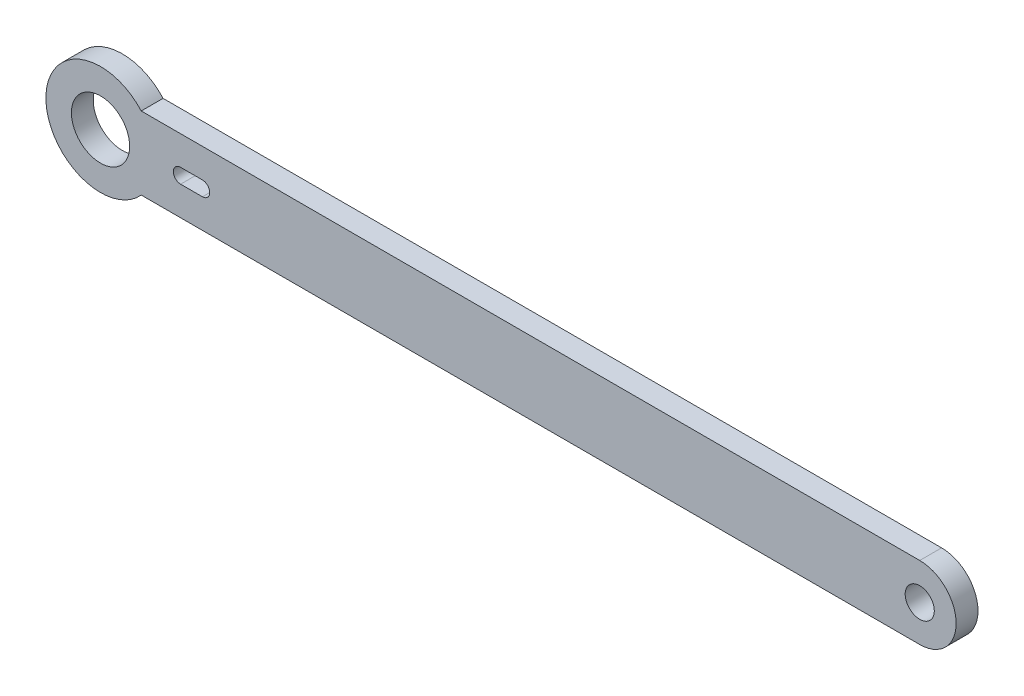
SolidWorks part; units mm, degrees
ref_plane "前视基准面" through (0, 0, 0) normal (0, 0, 1) x (1, 0, 0)
ref_plane "上视基准面" through (0, 0, 0) normal (0, 1, 0) x (1, 0, 0)
ref_plane "右视基准面" through (0, 0, 0) normal (1, 0, 0) x (0, 0, -1)
sketch "草图1" plane through (0, 0, 0) normal (0, 0, 1) x (1, 0, 0)
  line L0 (0, 0) -> (112.5, 0) construction
  line L1 (1.65, 0) -> (-1.65, 0) construction
  line L2 (5.5902, 5) -> (112.5, 5)
  line L3 (5.5902, -5) -> (112.5, -5)
  line L4 (11, 0) -> (14, 0) construction
  line L5 (11, 1) -> (14, 1)
  line L6 (11, -1) -> (14, -1)
  arc A1 (112.5, -5) -> (112.5, 5) centre (112.5, 0) ccw
  circle A2 centre (112.5, 0) radius 2
  circle A3 centre (0, 0) radius 4
  arc A4 (5.5902, 5) -> (5.5902, -5) centre (0, 0) ccw
  arc A5 (11, 1) -> (11, -1) centre (11, 0) ccw
  arc A6 (14, -1) -> (14, 1) centre (14, 0) ccw
  point P5 (56.25, 0)
  point P8 (12.5, 0)
  point P21 (10, 0)
  dimension "D1" = 10
extrude "凸台-拉伸1" add sketch "草图1" along normal mid plane 3
